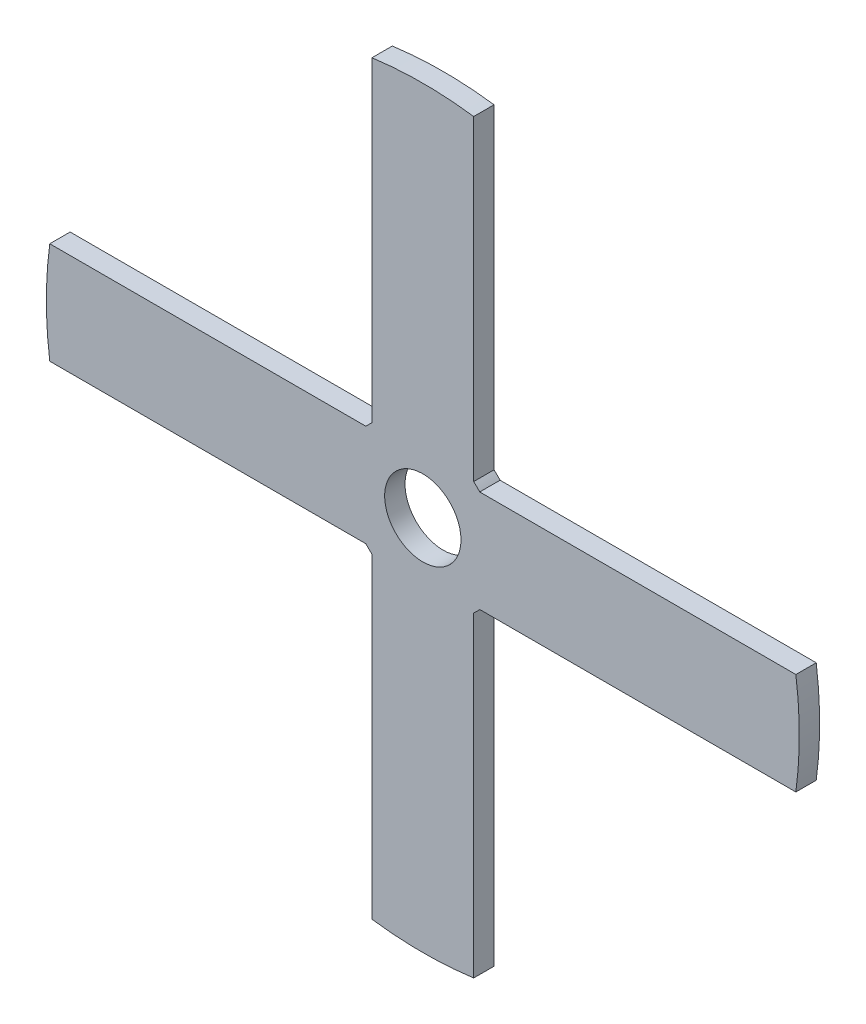
SolidWorks part; units mm, degrees
ref_plane "Front Plane" through (0, 0, 0) normal (0, 0, 1) x (1, 0, 0)
ref_plane "Top Plane" through (0, 0, 0) normal (0, 1, 0) x (1, 0, 0)
ref_plane "Right Plane" through (0, 0, 0) normal (1, 0, 0) x (0, 0, -1)
sketch "Sketch1" plane through (0, 0, 0) normal (0, 0, 1) x (1, 0, 0)
  line L0 (0, 15) -> (0, 180.4998) construction
  line L1 (20, 22.3607) -> (20, 146.6424)
  line L2 (-20, 22.3607) -> (-20, 146.6424)
  line L3 (22.3607, -20) -> (146.6424, -20)
  line L4 (20, 15) -> (20, 180.4998) construction
  line L5 (-20, 15) -> (-20, 180.4998) construction
  line L6 (22.3607, 20) -> (146.6424, 20)
  line L7 (-20, -22.3607) -> (-20, -146.6424)
  line L8 (20, -22.3607) -> (20, -146.6424)
  line L9 (-22.3607, 20) -> (-146.6424, 20)
  line L10 (-22.3607, -20) -> (-146.6424, -20)
  arc A0 (20, 146.6424) -> (-20, 146.6424) centre (0, 0) ccw
  circle A1 centre (0, 0) radius 15
  arc A2 (-20, 22.3607) -> (-22.3607, 20) centre (0, 0) ccw
  arc A3 (-22.3607, -20) -> (-20, -22.3607) centre (0, 0) ccw
  arc A4 (20, -22.3607) -> (22.3607, -20) centre (0, 0) ccw
  arc A5 (22.3607, 20) -> (20, 22.3607) centre (0, 0) ccw
  arc A6 (-146.6424, 20) -> (-146.6424, -20) centre (0, 0) ccw
  arc A7 (-20, -146.6424) -> (20, -146.6424) centre (0, 0) ccw
  arc A8 (146.6424, -20) -> (146.6424, 20) centre (0, 0) ccw
  point P30 (0, 0)
  dimension "D1" = 296
  dimension "D2" = 30
  dimension "D3" = 60
  dimension "D4" = 20
  dimension "D5" = 20
  dimension "D6" = 4
extrude "Boss-Extrude1" add sketch "Sketch1" along normal blind 8
